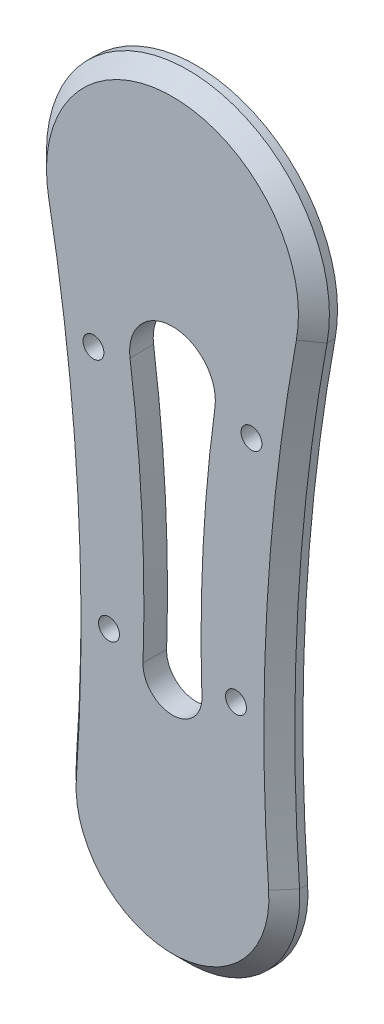
SolidWorks part; units mm, degrees
ref_plane "Front Plane" through (0, 0, 0) normal (0, 0, 1) x (1, 0, 0)
ref_plane "Top Plane" through (0, 0, 0) normal (0, 1, 0) x (1, 0, 0)
ref_plane "Right Plane" through (0, 0, 0) normal (1, 0, 0) x (0, 0, -1)
sketch "Sketch2" plane through (0, 0, 12.5727) normal (0, 0, 1) x (1, 0, 0)
  circle A0 centre (-19.5, 0) radius 2.7
extrude "Boss-Extrude1" add sketch "Sketch2" against normal blind 5 and the other way blind 7
sketch "Sketch4" plane through (0, 0, 19.5727) normal (0, 0, 1) x (1, 0, 0)
  arc A0 (16.4768, -6.6506) -> (-55.4768, -6.6506) centre (-19.5, 0) ccw
  arc A1 (-48.3671, -132.4551) -> (9.3671, -132.4551) centre (-19.5, -134.4759) ccw
  arc A2 (-48.3671, -132.4551) -> (-55.4768, -6.6506) centre (-547.1466, -97.5401) ccw
  arc A3 (9.3671, -132.4551) -> (16.4768, -6.6506) centre (508.1466, -97.5401) cw
extrude "Boss-Extrude3" add sketch "Sketch4" against normal blind 6 and the other way blind 0.1
chamfer "Chamfer1" distance 4 angle 45 4 edges at (8.9431, -69.328, 19.6727) (-19.5, 36.5864, 19.6727) (-19.5, -163.4136, 19.6727) (-47.9431, -69.328, 19.6727)
sketch "Sketch5" plane through (0, 0, 13.5727) normal (0, 0, -1) x (-1, 0, 0)
  circle A0 centre (19.5, -134.4759) radius 2.7
extrude "Boss-Extrude4" add sketch "Sketch5" along normal up to surface (6 mm away) up to face at (-16.8, 0, 7.5727)
sketch "Sketch6" plane through (0, 0, 13.5727) normal (0, 0, -1) x (-1, 0, 0)
  arc A0 (30.4877, -31.464) -> (8.5123, -31.464) centre (19.5, -29.9737) ccw
  arc A1 (11.89, -98.0751) -> (27.11, -98.0751) centre (19.5, -98.33) ccw
  arc A2 (30.4877, -31.464) -> (27.11, -98.0751) centre (423.6499, -84.7918) ccw
  arc A3 (8.5123, -31.464) -> (11.89, -98.0751) centre (-384.6499, -84.7918) cw
extrude "Cut-Extrude1" cut sketch "Sketch6" against normal blind 23
sketch "Sketch7" plane through (0, 0, 13.5727) normal (0, 0, -1) x (-1, 0, 0)
  circle A0 centre (39.9349, -33.6777) radius 2.7
  circle A1 centre (35.9208, -94.8134) radius 2.7
  circle A2 centre (-0.9349, -33.6777) radius 2.7
  circle A3 centre (3.0792, -94.8134) radius 2.7
extrude "Cut-Extrude2" cut sketch "Sketch7" against normal blind 37
sketch "Sketch8" plane through (0, 0, 13.5727) normal (0, 0, -1) x (-1, 0, 0)
  circle A0 centre (19.5, -134.4759) radius 6.25
  dimension "D1" = 12.5
extrude "Boss-Extrude5" add sketch "Sketch8" along normal blind 2.5
sketch "Sketch9" plane through (0, 0, 7.5727) normal (0, 0, -1) x (-1, 0, 0)
  circle A1 centre (19.5, -134.4759) radius 2.7
  circle A2 centre (19.5, -134.4759) radius 2.7
  dimension "D1" = 0
extrude "Boss-Extrude6" add sketch "Sketch9" along normal blind 4.5
